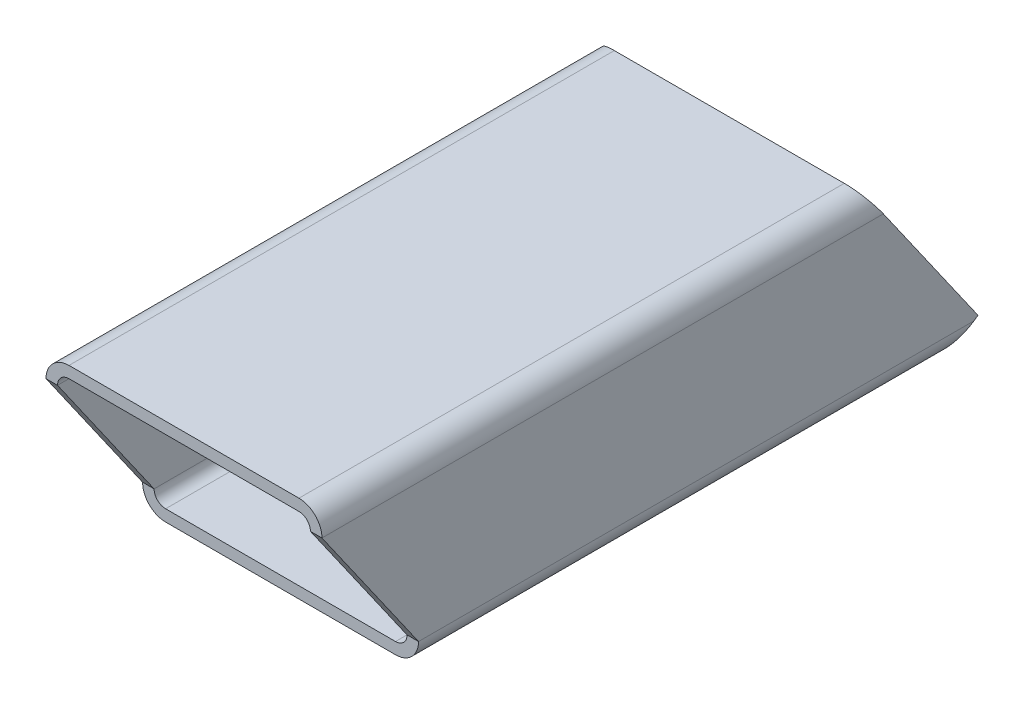
SolidWorks part; units mm, degrees
material "ASTM A36 Steel"
ref_plane "Front Plane" through (0, 0, 0) normal (0, 0, 1) x (1, 0, 0)
ref_plane "Top Plane" through (0, 0, 0) normal (0, 1, 0) x (1, 0, 0)
ref_plane "Right Plane" through (0, 0, 0) normal (1, 0, 0) x (0, 0, -1)
sketch "Sketch1" plane through (0, 0, 0) normal (0, 0, 1) x (1, 0, 0)
  line L0 (-63.5, 44.45) -> (63.5, 44.45)
  line L1 (-63.5, -50.8) -> (63.5, -50.8)
  line L2 (-76.2, -38.1) -> (-76.2, 38.1)
  line L3 (-63.5, 50.8) -> (63.5, 50.8)
  line L4 (76.2, -38.1) -> (76.2, 38.1)
  line L5 (-76.2, -50.8) -> (76.2, 50.8) construction
  line L6 (-76.2, 50.8) -> (76.2, -50.8) construction
  line L7 (69.85, -38.1) -> (69.85, 38.1)
  line L8 (-63.5, -44.45) -> (63.5, -44.45)
  line L9 (-69.85, -38.1) -> (-69.85, 38.1)
  arc A0 (63.5, -50.8) -> (76.2, -38.1) centre (63.5, -38.1) ccw
  arc A1 (-76.2, 38.1) -> (-63.5, 50.8) centre (-63.5, 38.1) cw
  arc A2 (-63.5, -50.8) -> (-76.2, -38.1) centre (-63.5, -38.1) cw
  arc A3 (63.5, 50.8) -> (76.2, 38.1) centre (63.5, 38.1) cw
  arc A4 (63.5, 44.45) -> (69.85, 38.1) centre (63.5, 38.1) cw
  arc A5 (63.5, -44.45) -> (69.85, -38.1) centre (63.5, -38.1) ccw
  arc A6 (-63.5, -44.45) -> (-69.85, -38.1) centre (-63.5, -38.1) cw
  arc A7 (-69.85, 38.1) -> (-63.5, 44.45) centre (-63.5, 38.1) cw
  point P0 (0, 0)
  dimension "D3" = 12.7
  dimension "D1" = 152.4
  dimension "D2" = 101.6
  dimension "D4" = 6.35
extrude "Boss-Extrude1" add sketch "Sketch1" along normal mid plane 431.8
sketch "Sketch2" plane through (0, 0, 0) normal (1, 0, 0) x (0, 0, -1)
  line L0 (-215.9, 50.8) -> (-215.9, -50.8)
  line L1 (-215.9, -50.8) -> (-159.3692, -50.8)
  line L2 (-215.9, -50.8) -> (215.9, -50.8) construction
  line L3 (-159.3692, -50.8) -> (-159.3692, -38.1)
  line L4 (-159.3692, -38.1) -> (-212.725, 38.1)
  line L5 (-215.9, 38.1) -> (215.9, 38.1) construction
  line L6 (-212.725, 38.1) -> (-212.725, 50.8)
  line L7 (-212.725, 50.8) -> (-215.9, 50.8)
  dimension "D1" = 3.175
  dimension "D2" = 35
  dimension "D3" = 12.7
extrude "Cut-Extrude1" cut sketch "Sketch2" against normal through all and the other way through all
sketch "Sketch3" plane through (0, 0, 0) normal (1, 0, 0) x (0, 0, -1)
  line L0 (70.3287, 76.6929) -> (183.8552, -85.4397) construction
  line L1 (-159.3692, -38.1) -> (-212.725, 38.1) construction
  line L2 (70.3287, 76.6929) -> (278.8757, 76.6929)
  line L3 (278.8757, 76.6929) -> (278.8757, -66.3535)
  line L4 (278.8757, -66.3535) -> (183.8552, -85.4397)
  line L5 (183.8552, -85.4397) -> (70.3287, 76.6929)
  dimension "D1" = 254
extrude "Cut-Extrude2" cut sketch "Sketch3" against normal through all and the other way through all
sketch "Sketch4" plane through (76.2, 0, 0) normal (1, 0, 0) x (0, 0, -1)
  line L0 (51.6671, -105.1353) -> (172.4435, -20.5668)
  line L1 (97.3517, 38.1) -> (150.7076, -38.1) construction
  line L2 (51.6671, -105.1353) -> (188.2438, -73.4347)
  line L3 (188.2438, -73.4347) -> (172.4435, -20.5668)
  dimension "D1" = 17.399
extrude "Cut-Extrude3" cut sketch "Sketch4" against normal through all and the other way through all
equation "\"PRIMER_USAGE\"= ( \"SW-SurfaceArea\" / 144 ) / 135"
equation "\"WET_PAINT_USAGE\"= ( \"SW-SurfaceArea\" / 144 ) / 125"
equation "\"POWDERCOAT_USAGE\"= ( \"SW-SurfaceArea\" / 144 ) / 29.79"
equation "\"DECKOVER_USAGE\"= ( \"SW-SurfaceArea\" / 144 ) / 75"
equation "\"SW_NON-SKID\"= ( \"SW-SurfaceArea\" / 144 ) / 165"
equation "\"TYPE_1_ANODIZATING\"= ( \"SW-SurfaceArea\" * 0.0001 )"
equation "\"TYPE_2_ANODIZING\"= ( \"SW-SurfaceArea\" * 0.0005 )"
equation "\"TYPE_3_ANODIZING-HARDCOAT\"= ( \"SW-SurfaceArea\" * 0.003 )"
